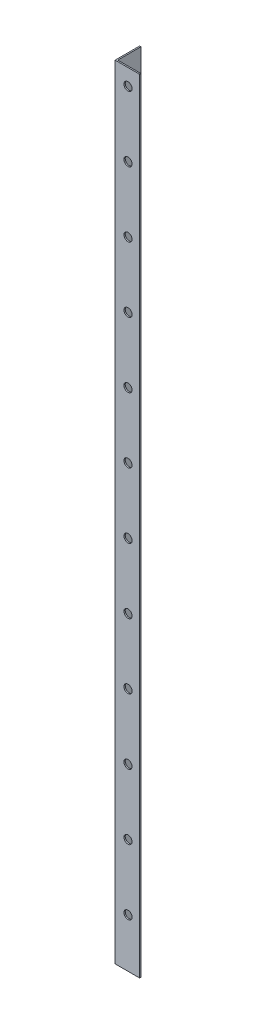
SolidWorks part; units mm, degrees
ref_plane "Front Plane" through (0, 0, 0) normal (0, 0, 1) x (1, 0, 0)
ref_plane "Top Plane" through (0, 0, 0) normal (0, 1, 0) x (1, 0, 0)
ref_plane "Right Plane" through (0, 0, 0) normal (1, 0, 0) x (0, 0, -1)
sketch "Sketch2" plane through (0, 0, 0) normal (0, 1, 0) x (1, 0, 0)
  line L0 (0, 0) -> (9.525, 0)
  line L1 (9.525, 0) -> (9.525, 0.508)
  line L2 (9.525, 0.508) -> (0.508, 0.508)
  line L3 (0.508, 0.508) -> (0.508, 9.525)
  line L4 (0.508, 9.525) -> (0, 9.525)
  line L5 (0, 9.525) -> (0, 0)
  dimension "D1" = 9.525
  dimension "D3" = 0.508
extrude "Boss-Extrude1" add sketch "Sketch2" along normal blind 304.8
sketch "Sketch3" plane through (0, 0, -0.508) normal (0, 0, -1) x (-1, 0, 0)
  line L0 (-9.525, 304.8) -> (-0.508, 304.8) construction
  circle A0 centre (-5.0165, 298.45) radius 1.5875
  point P4 (0, 0)
  point P5 (-5.0165, 304.8)
  dimension "D2" = 3.175
  dimension "D1" = 6.35
extrude "Cut-Extrude1" cut sketch "Sketch3" against normal through all
pattern_linear "LPattern1" count 12 spacing 25.4 along (0, -1, 0) of "Cut-Extrude1"
sketch "Sketch4" plane through (0.508, 0, 0) normal (1, 0, 0) x (0, 0, -1)
  line L0 (0.508, 304.8) -> (9.525, 304.8) construction
  circle A0 centre (5.0165, 285.75) radius 1.5875
  point P4 (0, 0)
  point P5 (5.0165, 304.8)
  dimension "D2" = 3.175
  dimension "D1" = 19.05
extrude "Cut-Extrude2" cut sketch "Sketch4" against normal through all
pattern_linear "LPattern2" count 12 spacing 25.4 along (0, -1, 0) of "Cut-Extrude2"
